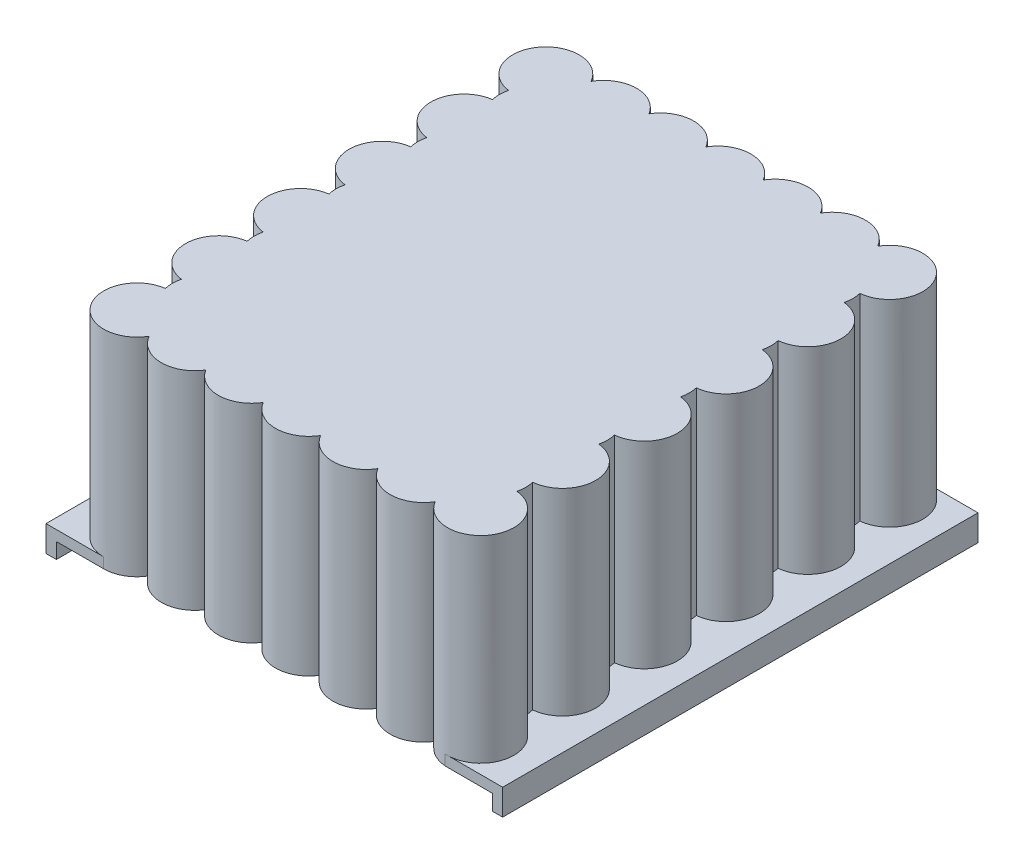
SolidWorks part; units mm, degrees
material "Titanium Ti-5Al-2.5Sn"
ref_plane "Front Plane" through (0, 0, 0) normal (0, 0, 1) x (1, 0, 0)
ref_plane "Top Plane" through (0, 0, 0) normal (0, 1, 0) x (1, 0, 0)
ref_plane "Right Plane" through (0, 0, 0) normal (1, 0, 0) x (0, 0, -1)
sketch "Sketch2" plane through (0, 0, 0) normal (0, 1, 0) x (1, 0, 0)
  circle A0 centre (-104.3845, 125.3413) radius 14
  circle A1 centre (-69.3845, 125.3413) radius 14
  circle A2 centre (-34.3845, 125.3413) radius 14
  circle A3 centre (0.6155, 125.3413) radius 14
  circle A4 centre (35.6155, 125.3413) radius 14
  circle A5 centre (70.6155, 125.3413) radius 14
  circle A6 centre (105.6155, 125.3413) radius 14
  circle A7 centre (-69.3845, 75.3413) radius 14
  circle A8 centre (-34.3845, 75.3413) radius 14
  circle A9 centre (0.6155, 75.3413) radius 14
  circle A10 centre (35.6155, 75.3413) radius 14
  circle A11 centre (70.6155, 75.3413) radius 14
  circle A12 centre (105.6155, 75.3413) radius 14
  circle A13 centre (-69.3845, 25.3413) radius 14
  circle A14 centre (-34.3845, 25.3413) radius 14
  circle A15 centre (0.6155, 25.3413) radius 14
  circle A16 centre (35.6155, 25.3413) radius 14
  circle A17 centre (70.6155, 25.3413) radius 14
  circle A18 centre (105.6155, 25.3413) radius 14
  circle A19 centre (-69.3845, -24.6587) radius 14
  circle A20 centre (-34.3845, -24.6587) radius 14
  circle A21 centre (0.6155, -24.6587) radius 14
  circle A22 centre (35.6155, -24.6587) radius 14
  circle A23 centre (70.6155, -24.6587) radius 14
  circle A24 centre (105.6155, -24.6587) radius 14
  circle A25 centre (-69.3845, -74.6587) radius 14
  circle A26 centre (-34.3845, -74.6587) radius 14
  circle A27 centre (0.6155, -74.6587) radius 14
  circle A28 centre (35.6155, -74.6587) radius 14
  circle A29 centre (70.6155, -74.6587) radius 14
  circle A30 centre (105.6155, -74.6587) radius 14
  circle A31 centre (-69.3845, -124.6587) radius 14
  circle A32 centre (-34.3845, -124.6587) radius 14
  circle A33 centre (0.6155, -124.6587) radius 14
  circle A34 centre (35.6155, -124.6587) radius 14
  circle A35 centre (70.6155, -124.6587) radius 14
  circle A36 centre (105.6155, -124.6587) radius 14
  circle A37 centre (-104.3845, 75.3413) radius 14
  circle A38 centre (-104.3845, 25.3413) radius 14
  circle A39 centre (-104.3845, -24.6587) radius 14
  circle A40 centre (-104.3845, -74.6587) radius 14
  circle A41 centre (-104.3845, -124.6587) radius 14
  circle A42 centre (-87.3845, 100.3413) radius 14
  circle A43 centre (-52.3845, 100.3413) radius 14
  circle A44 centre (-17.3845, 100.3413) radius 14
  circle A45 centre (17.6155, 100.3413) radius 14
  circle A46 centre (52.6155, 100.3413) radius 14
  circle A47 centre (87.6155, 100.3413) radius 14
  circle A48 centre (-52.3845, 50.3413) radius 14
  circle A49 centre (-17.3845, 50.3413) radius 14
  circle A50 centre (17.6155, 50.3413) radius 14
  circle A51 centre (52.6155, 50.3413) radius 14
  circle A52 centre (87.6155, 50.3413) radius 14
  circle A53 centre (-52.3845, 0.3413) radius 14
  circle A54 centre (-17.3845, 0.3413) radius 14
  circle A55 centre (17.6155, 0.3413) radius 14
  circle A56 centre (52.6155, 0.3413) radius 14
  circle A57 centre (87.6155, 0.3413) radius 14
  circle A58 centre (-52.3845, -49.6587) radius 14
  circle A59 centre (-17.3845, -49.6587) radius 14
  circle A60 centre (17.6155, -49.6587) radius 14
  circle A61 centre (52.6155, -49.6587) radius 14
  circle A62 centre (87.6155, -49.6587) radius 14
  circle A63 centre (-52.3845, -99.6587) radius 14
  circle A64 centre (-17.3845, -99.6587) radius 14
  circle A65 centre (17.6155, -99.6587) radius 14
  circle A66 centre (52.6155, -99.6587) radius 14
  circle A67 centre (87.6155, -99.6587) radius 14
  circle A68 centre (-87.3845, 50.3413) radius 14
  circle A69 centre (-87.3845, 0.3413) radius 14
  circle A70 centre (-87.3845, -49.6587) radius 14
  circle A71 centre (-87.3845, -99.6587) radius 14
sketch "Sketch3" plane through (0, 0, 0) normal (0, 1, 0) x (1, 0, 0)
  line L1 (-132.3198, 152.7914) -> (134.3802, 152.7914)
  line L2 (-132.3198, 152.7914) -> (-132.3198, -152.0086)
  line L3 (-132.3198, -152.0086) -> (134.3802, -152.0086)
  line L4 (134.3802, 152.7914) -> (134.3802, -152.0086)
  dimension "D1" = 304.8
  dimension "D2" = 266.7
extrude "Boss-Extrude1" add sketch "Sketch3" along normal blind 127
extrude "Cut-Extrude1" cut sketch "Sketch2" along normal blind 101.6
sketch "Sketch4" plane through (0, 0, 0) normal (0, -1, 0) x (1, 0, 0)
  line L1 (-132.3198, 152.0086) -> (134.3802, 152.0086)
  line L2 (-132.3198, 152.0086) -> (-132.3198, -152.7914)
  line L3 (-132.3198, -152.7914) -> (134.3802, -152.7914)
  line L4 (134.3802, 152.0086) -> (134.3802, -152.7914)
  arc A0 (-86.7752, 134.7985) -> (-107.1138, 104.5229) centre (-104.3845, 124.6587) ccw
  arc A5 (-16.7545, 114.3757) -> (-1.7647, 104.4976) centre (0.7715, 124.6587) ccw
  arc A7 (51.1245, 119.8835) -> (90.6148, 119.8357) centre (70.8755, 124.6587) ccw
  arc A8 (86.1781, 119.8771) -> (88.4015, 114.3757) centre (105.9275, 124.6587) ccw
  arc A9 (-49.6103, 79.513) -> (-51.8065, 84.9038) centre (-69.3325, 74.6207) ccw
  arc A10 (-51.8065, 84.9038) -> (-54.0268, 79.4152) centre (-34.2805, 74.6207) ccw
  arc A12 (33.3518, 54.4516) -> (33.3609, 94.791) centre (35.8235, 74.6207) ccw
  circle A13 centre (70.8755, 74.6207) radius 20.32
  arc A14 (88.4015, 84.9038) -> (88.4015, 64.3377) centre (105.9275, 74.6207) ccw
  arc A15 (-86.8585, 14.2997) -> (-84.6553, 19.7186) centre (-104.3845, 24.5827) ccw
  arc A16 (-89.0802, 29.3716) -> (-49.6012, 19.7272) centre (-69.3325, 24.5827) ccw
  arc A19 (16.071, 19.8137) -> (37.7142, 44.8146) centre (35.8235, 24.5827) ccw
  circle A20 centre (70.8755, 24.5827) radius 20.32
  arc A21 (88.4015, 34.8658) -> (88.4015, 14.2997) centre (105.9275, 24.5827) ccw
  arc A22 (-86.8585, -35.7383) -> (-86.8585, -15.1722) centre (-104.3845, -25.4553) ccw
  circle A23 centre (-69.3325, -25.4553) radius 20.32
  circle A24 centre (-34.2805, -25.4553) radius 20.32
  circle A25 centre (0.7715, -25.4553) radius 20.32
  circle A26 centre (35.8235, -25.4553) radius 20.32
  arc A27 (90.6057, -20.5953) -> (88.4015, -35.7383) centre (70.8755, -25.4553) ccw
  arc A28 (88.4015, -15.1722) -> (88.4015, -35.7383) centre (105.9275, -25.4553) ccw
  arc A29 (-86.8585, -85.7763) -> (-86.8585, -65.2102) centre (-104.3845, -75.4933) ccw
  circle A30 centre (-69.3325, -75.4933) radius 20.32
  circle A31 centre (-34.2805, -75.4933) radius 20.32
  circle A32 centre (0.7715, -75.4933) radius 20.32
  circle A33 centre (35.8235, -75.4933) radius 20.32
  circle A34 centre (70.8755, -75.4933) radius 20.32
  arc A35 (88.4015, -65.2102) -> (88.4015, -85.7763) centre (105.9275, -75.4933) ccw
  arc A36 (-84.6644, -120.6304) -> (-86.6147, -115.6754) centre (-104.3845, -125.5313) ccw
  arc A37 (-49.4244, -120.6136) -> (-88.6164, -120.7759) centre (-69.0004, -125.5313) ccw
  arc A38 (-14.5562, -120.6473) -> (-54.0268, -120.7368) centre (-34.2805, -125.5313) ccw
  arc A39 (20.4978, -120.6555) -> (-18.9734, -120.7311) centre (0.7715, -125.5313) ccw
  arc A40 (55.5518, -120.6635) -> (16.08, -120.7251) centre (35.8235, -125.5313) ccw
  arc A41 (90.6057, -120.6713) -> (51.1336, -120.7189) centre (70.8755, -125.5313) ccw
  arc A42 (88.4015, -115.2482) -> (86.1871, -120.7126) centre (105.9275, -125.5313) ccw
  arc A43 (-107.1138, 104.5229) -> (-107.1047, 94.7578) centre (-87.3845, 99.6587) ccw
  arc A44 (-54.0268, 79.4152) -> (-34.7069, 89.4325) centre (-52.2661, 99.6587) ccw
  arc A47 (33.3609, 94.791) -> (35.53, 109.885) centre (53.0892, 99.6587) ccw
  arc A48 (90.6148, 119.8357) -> (90.6057, 79.4807) centre (88.2076, 99.6587) ccw
  arc A49 (-89.0802, 29.3716) -> (-84.6644, 29.4836) centre (-87.3845, 49.6207) ccw
  arc A50 (-69.8253, 59.847) -> (-71.9974, 54.4762) centre (-52.2661, 49.6207) ccw
  arc A51 (-34.7069, 59.847) -> (-36.8811, 54.4678) centre (-17.1477, 49.6207) ccw
  arc A52 (35.53, 39.3945) -> (33.3518, 54.4516) centre (53.0892, 49.6207) ccw
  arc A53 (90.6148, 69.7977) -> (90.6057, 29.4427) centre (88.2076, 49.6207) ccw
  arc A54 (20.4978, 29.4585) -> (35.53, 39.3945) centre (17.9708, 49.6207) ccw
  arc A55 (-89.0802, -20.6664) -> (-89.0891, 19.8311) centre (-87.3845, -0.4173) ccw
  circle A56 centre (-52.2661, -0.4173) radius 20.32
  arc A57 (-14.5471, 19.7356) -> (-18.9824, 19.8197) centre (-17.1477, -0.4173) ccw
  circle A58 centre (53.0892, -0.4173) radius 20.32
  arc A59 (90.6148, 19.7597) -> (90.6057, -20.5953) centre (88.2076, -0.4173) ccw
  circle A60 centre (17.9708, -0.4173) radius 20.32
  arc A61 (-89.0802, -70.7044) -> (-89.0891, -30.2069) centre (-87.3845, -50.4553) ccw
  circle A62 centre (-52.2661, -50.4553) radius 20.32
  circle A63 centre (-17.1477, -50.4553) radius 20.32
  circle A64 centre (53.0892, -50.4553) radius 20.32
  arc A65 (86.1781, -30.2369) -> (90.6057, -70.6333) centre (88.2076, -50.4553) ccw
  circle A66 centre (17.9708, -50.4553) radius 20.32
  arc A67 (-88.6164, -120.7759) -> (-89.0891, -80.2449) centre (-87.3845, -100.4933) ccw
  circle A68 centre (-52.2661, -100.4933) radius 20.32
  circle A69 centre (-17.1477, -100.4933) radius 20.32
  circle A70 centre (53.0892, -100.4933) radius 20.32
  arc A71 (90.6148, -80.3163) -> (90.6057, -120.6713) centre (88.2076, -100.4933) ccw
  circle A72 centre (17.9708, -100.4933) radius 20.32
  arc A74 (-89.0891, 119.9071) -> (-86.8585, 114.3757) centre (-69.3325, 124.6587) ccw
  arc A76 (-32.5108, 104.4159) -> (-34.7069, 109.885) centre (-52.2661, 99.6587) ccw
  arc A78 (-67.6279, 54.3724) -> (-69.8253, 59.847) centre (-87.3845, 49.6207) ccw
  arc A79 (-67.6369, 44.8319) -> (-71.9884, 44.7284) centre (-69.3325, 24.5827) ccw
  arc A80 (-49.6103, 29.475) -> (-51.8065, 34.8658) centre (-69.3325, 24.5827) ccw
  arc A81 (-1.7556, 94.783) -> (0.4116, 89.4325) centre (17.9708, 99.6587) ccw
  arc A82 (-34.7069, 109.885) -> (-36.8811, 104.5058) centre (-17.1477, 99.6587) ccw
  arc A83 (-54.0358, 19.8255) -> (-16.7545, 14.2997) centre (-34.2805, 24.5827) ccw
  arc A84 (-36.8811, 104.5058) -> (-32.5108, 104.4159) centre (-34.2805, 124.6587) ccw
  arc A85 (-51.5561, 135.3572) -> (-86.7752, 134.7985) centre (-69.0004, 124.6587) ccw
  arc A86 (-16.7545, 134.9418) -> (-51.5561, 135.3572) centre (-34.2805, 124.6587) ccw
  arc A87 (18.2975, 134.9418) -> (-16.7545, 134.9418) centre (0.7715, 124.6587) ccw
  arc A88 (53.3495, 134.9418) -> (18.2975, 134.9418) centre (35.8235, 124.6587) ccw
  arc A89 (88.4015, 134.9418) -> (53.3495, 134.9418) centre (70.8755, 124.6587) ccw
  arc A90 (107.957, 104.4403) -> (88.4015, 134.9418) centre (105.9275, 124.6587) ccw
  arc A91 (107.948, 94.84) -> (107.957, 104.4403) centre (88.2076, 99.6587) ccw
  arc A92 (107.957, 54.4023) -> (107.948, 94.84) centre (105.9275, 74.6207) ccw
  arc A93 (107.948, 44.802) -> (107.957, 54.4023) centre (88.2076, 49.6207) ccw
  arc A94 (107.957, 4.3643) -> (107.948, 44.802) centre (105.9275, 24.5827) ccw
  arc A95 (107.948, -5.236) -> (107.957, 4.3643) centre (88.2076, -0.4173) ccw
  arc A96 (107.957, -45.6737) -> (107.948, -5.236) centre (105.9275, -25.4553) ccw
  arc A97 (107.948, -55.274) -> (107.957, -45.6737) centre (88.2076, -50.4553) ccw
  arc A98 (107.957, -95.7117) -> (107.948, -55.274) centre (105.9275, -75.4933) ccw
  arc A99 (107.948, -105.312) -> (107.957, -95.7117) centre (88.2076, -100.4933) ccw
  arc A100 (88.4015, -135.8143) -> (107.948, -105.312) centre (105.9275, -125.5313) ccw
  arc A101 (53.3495, -135.8143) -> (88.4015, -135.8143) centre (70.8755, -125.5313) ccw
  arc A102 (18.2975, -135.8143) -> (53.3495, -135.8143) centre (35.8235, -125.5313) ccw
  arc A103 (-16.7545, -135.8143) -> (18.2975, -135.8143) centre (0.7715, -125.5313) ccw
  arc A104 (-51.7196, -135.961) -> (-16.7545, -135.8143) centre (-34.2805, -125.5313) ccw
  arc A105 (-86.6147, -135.3871) -> (-51.7196, -135.961) centre (-69.0004, -125.5313) ccw
  arc A106 (-107.1047, -105.3942) -> (-86.6147, -135.3871) centre (-104.3845, -125.5313) ccw
  arc A107 (-107.1138, -95.6291) -> (-107.1047, -105.3942) centre (-87.3845, -100.4933) ccw
  arc A108 (-107.1047, -55.3562) -> (-107.1138, -95.6291) centre (-104.3845, -75.4933) ccw
  arc A109 (-107.1138, -45.5911) -> (-107.1047, -55.3562) centre (-87.3845, -50.4553) ccw
  arc A110 (-107.1047, -5.3182) -> (-107.1138, -45.5911) centre (-104.3845, -25.4553) ccw
  arc A111 (-107.1138, 4.4469) -> (-107.1047, -5.3182) centre (-87.3845, -0.4173) ccw
  arc A112 (-107.1047, 44.7198) -> (-107.1138, 4.4469) centre (-104.3845, 24.5827) ccw
  arc A113 (-107.1138, 54.4849) -> (-107.1047, 44.7198) centre (-87.3845, 49.6207) ccw
  arc A114 (-34.7069, 9.809) -> (0.4116, 9.809) centre (-17.1477, -0.4173) ccw
  arc A115 (-107.1047, 94.7578) -> (-107.1138, 54.4849) centre (-104.3845, 74.6207) ccw
  arc A116 (-16.7545, 114.3757) -> (-14.5471, 119.8116) centre (-34.2805, 124.6587) ccw
  arc A117 (0.4116, 109.885) -> (-1.7647, 104.4976) centre (17.9708, 99.6587) ccw
  arc A119 (37.7232, 104.4277) -> (55.5609, 119.8278) centre (35.8235, 124.6587) ccw
  arc A120 (-34.7069, 89.4325) -> (-18.9734, 79.4209) centre (-17.1477, 99.6587) ccw
  arc A122 (20.5069, 69.7818) -> (20.4978, 79.4965) centre (0.7715, 74.6207) ccw
  arc A124 (-14.5471, 69.7736) -> (-18.9824, 69.8577) centre (-17.1477, 49.6207) ccw
  arc A125 (-54.0358, 69.8635) -> (-32.5108, 54.3779) centre (-34.2805, 74.6207) ccw
  arc A127 (-71.9974, 54.4762) -> (-67.6279, 54.3724) centre (-69.3325, 74.6207) ccw
  arc A132 (-86.8585, 64.3377) -> (-84.6553, 69.7566) centre (-104.3845, 74.6207) ccw
  arc A133 (-51.8065, 64.3377) -> (-49.6012, 69.7652) centre (-69.3325, 74.6207) ccw
  arc A134 (-18.9734, 29.3829) -> (-14.5562, 29.4667) centre (-17.1477, 49.6207) ccw
  arc A135 (-32.5108, 54.3779) -> (-54.0358, 69.8635) centre (-52.2661, 49.6207) ccw
  arc A137 (37.7142, 44.8146) -> (35.53, 59.847) centre (17.9708, 49.6207) ccw
  arc A139 (33.3609, 44.753) -> (18.2975, 34.8658) centre (35.8235, 24.5827) ccw
  arc A140 (-16.7545, 14.2997) -> (20.4978, 29.4585) centre (0.7715, 24.5827) ccw
  arc A141 (20.5069, 69.7818) -> (-1.7647, 54.4596) centre (17.9708, 49.6207) ccw
  arc A142 (35.53, 89.4325) -> (37.7232, 104.4277) centre (17.9708, 99.6587) ccw
  arc A145 (-18.9824, 69.8577) -> (-16.7545, 64.3377) centre (0.7715, 74.6207) ccw
  arc A146 (16.08, 79.4269) -> (20.4978, 79.4965) centre (17.9708, 99.6587) ccw
  arc A148 (16.071, 119.8897) -> (18.2975, 114.3757) centre (35.8235, 124.6587) ccw
  arc A149 (-16.7545, 34.8658) -> (-18.9734, 29.3829) centre (0.7715, 24.5827) ccw
  point P8 (0, 0)
  dimension "D1" = 40.64
  dimension "D2" = 7
  dimension "D4" = 40.64
  dimension "D3" = 6
  dimension "D5" = 6
  dimension "D6" = 5
sketch "Sketch5" plane through (0, 0, 0) normal (0, -1, 0) x (1, 0, 0)
  line L0 (-132.3198, 152.0086) -> (-132.3198, -152.7914) construction
  line L1 (-132.3198, -152.7914) -> (134.3802, -152.7914) construction
  line L2 (134.3802, 152.0086) -> (134.3802, -152.7914) construction
  line L3 (-132.3198, 152.0086) -> (134.3802, 152.0086) construction
  line L4 (-132.3198, 152.0086) -> (-132.3198, -152.7914)
  line L5 (-132.3198, -152.7914) -> (134.3802, -152.7914)
  line L6 (134.3802, 152.0086) -> (134.3802, -152.7914)
  line L7 (-132.3198, 152.0086) -> (134.3802, 152.0086)
  arc A0 (-86.7752, 134.7985) -> (-107.1138, 104.5229) centre (-104.3845, 124.6587) ccw construction
  arc A1 (-107.1138, 104.5229) -> (-107.1047, 94.7578) centre (-87.3845, 99.6587) ccw construction
  arc A2 (-107.1047, 94.7578) -> (-107.1138, 54.4849) centre (-104.3845, 74.6207) ccw construction
  arc A3 (-107.1138, 54.4849) -> (-107.1047, 44.7198) centre (-87.3845, 49.6207) ccw construction
  arc A4 (-107.1047, 44.7198) -> (-107.1138, 4.4469) centre (-104.3845, 24.5827) ccw construction
  arc A5 (-107.1138, 4.4469) -> (-107.1047, -5.3182) centre (-87.3845, -0.4173) ccw construction
  arc A6 (-107.1047, -5.3182) -> (-107.1138, -45.5911) centre (-104.3845, -25.4553) ccw construction
  arc A7 (-107.1138, -45.5911) -> (-107.1047, -55.3562) centre (-87.3845, -50.4553) ccw construction
  arc A8 (-107.1047, -55.3562) -> (-107.1138, -95.6291) centre (-104.3845, -75.4933) ccw construction
  arc A9 (-107.1138, -95.6291) -> (-107.1047, -105.3942) centre (-87.3845, -100.4933) ccw construction
  arc A10 (-107.1047, -105.3942) -> (-86.6147, -135.3871) centre (-104.3845, -125.5313) ccw construction
  arc A11 (-86.6147, -135.3871) -> (-51.7196, -135.961) centre (-69.0004, -125.5313) ccw construction
  arc A12 (-51.7196, -135.961) -> (-16.7545, -135.8143) centre (-34.2805, -125.5313) ccw construction
  arc A13 (-16.7545, -135.8143) -> (18.2975, -135.8143) centre (0.7715, -125.5313) ccw construction
  arc A14 (18.2975, -135.8143) -> (53.3495, -135.8143) centre (35.8235, -125.5313) ccw construction
  arc A15 (53.3495, -135.8143) -> (88.4015, -135.8143) centre (70.8755, -125.5313) ccw construction
  arc A16 (88.4015, -135.8143) -> (107.948, -105.312) centre (105.9275, -125.5313) ccw construction
  arc A17 (107.948, -105.312) -> (107.957, -95.7117) centre (88.2076, -100.4933) ccw construction
  arc A18 (107.957, -95.7117) -> (107.948, -55.274) centre (105.9275, -75.4933) ccw construction
  arc A19 (107.948, -55.274) -> (107.957, -45.6737) centre (88.2076, -50.4553) ccw construction
  arc A20 (107.957, -45.6737) -> (107.948, -5.236) centre (105.9275, -25.4553) ccw construction
  arc A21 (107.948, -5.236) -> (107.957, 4.3643) centre (88.2076, -0.4173) ccw construction
  arc A22 (107.957, 4.3643) -> (107.948, 44.802) centre (105.9275, 24.5827) ccw construction
  arc A23 (107.948, 44.802) -> (107.957, 54.4023) centre (88.2076, 49.6207) ccw construction
  arc A24 (107.957, 54.4023) -> (107.948, 94.84) centre (105.9275, 74.6207) ccw construction
  arc A25 (107.948, 94.84) -> (107.957, 104.4403) centre (88.2076, 99.6587) ccw construction
  arc A26 (107.957, 104.4403) -> (88.4015, 134.9418) centre (105.9275, 124.6587) ccw construction
  arc A27 (88.4015, 134.9418) -> (53.3495, 134.9418) centre (70.8755, 124.6587) ccw construction
  arc A28 (53.3495, 134.9418) -> (18.2975, 134.9418) centre (35.8235, 124.6587) ccw construction
  arc A29 (18.2975, 134.9418) -> (-16.7545, 134.9418) centre (0.7715, 124.6587) ccw construction
  arc A30 (-16.7545, 134.9418) -> (-51.5561, 135.3572) centre (-34.2805, 124.6587) ccw construction
  arc A31 (-51.5561, 135.3572) -> (-86.7752, 134.7985) centre (-69.0004, 124.6587) ccw construction
  arc A32 (-86.7752, 134.7985) -> (-107.1138, 104.5229) centre (-104.3845, 124.6587) ccw
  arc A33 (-107.1138, 104.5229) -> (-107.1047, 94.7578) centre (-87.3845, 99.6587) ccw
  arc A34 (-107.1047, 94.7578) -> (-107.1138, 54.4849) centre (-104.3845, 74.6207) ccw
  arc A35 (-107.1138, 54.4849) -> (-107.1047, 44.7198) centre (-87.3845, 49.6207) ccw
  arc A36 (-107.1047, 44.7198) -> (-107.1138, 4.4469) centre (-104.3845, 24.5827) ccw
  arc A37 (-107.1138, 4.4469) -> (-107.1047, -5.3182) centre (-87.3845, -0.4173) ccw
  arc A38 (-107.1047, -5.3182) -> (-107.1138, -45.5911) centre (-104.3845, -25.4553) ccw
  arc A39 (-107.1138, -45.5911) -> (-107.1047, -55.3562) centre (-87.3845, -50.4553) ccw
  arc A40 (-107.1047, -55.3562) -> (-107.1138, -95.6291) centre (-104.3845, -75.4933) ccw
  arc A41 (-107.1138, -95.6291) -> (-107.1047, -105.3942) centre (-87.3845, -100.4933) ccw
  arc A42 (-107.1047, -105.3942) -> (-86.6147, -135.3871) centre (-104.3845, -125.5313) ccw
  arc A43 (-86.6147, -135.3871) -> (-51.7196, -135.961) centre (-69.0004, -125.5313) ccw
  arc A44 (-51.7196, -135.961) -> (-16.7545, -135.8143) centre (-34.2805, -125.5313) ccw
  arc A45 (-16.7545, -135.8143) -> (18.2975, -135.8143) centre (0.7715, -125.5313) ccw
  arc A46 (18.2975, -135.8143) -> (53.3495, -135.8143) centre (35.8235, -125.5313) ccw
  arc A47 (53.3495, -135.8143) -> (88.4015, -135.8143) centre (70.8755, -125.5313) ccw
  arc A48 (88.4015, -135.8143) -> (107.948, -105.312) centre (105.9275, -125.5313) ccw
  arc A49 (107.948, -105.312) -> (107.957, -95.7117) centre (88.2076, -100.4933) ccw
  arc A50 (107.957, -95.7117) -> (107.948, -55.274) centre (105.9275, -75.4933) ccw
  arc A51 (107.948, -55.274) -> (107.957, -45.6737) centre (88.2076, -50.4553) ccw
  arc A52 (107.957, -45.6737) -> (107.948, -5.236) centre (105.9275, -25.4553) ccw
  arc A53 (107.948, -5.236) -> (107.957, 4.3643) centre (88.2076, -0.4173) ccw
  arc A54 (107.957, 4.3643) -> (107.948, 44.802) centre (105.9275, 24.5827) ccw
  arc A55 (107.948, 44.802) -> (107.957, 54.4023) centre (88.2076, 49.6207) ccw
  arc A56 (107.957, 54.4023) -> (107.948, 94.84) centre (105.9275, 74.6207) ccw
  arc A57 (107.948, 94.84) -> (107.957, 104.4403) centre (88.2076, 99.6587) ccw
  arc A58 (107.957, 104.4403) -> (88.4015, 134.9418) centre (105.9275, 124.6587) ccw
  arc A59 (88.4015, 134.9418) -> (53.3495, 134.9418) centre (70.8755, 124.6587) ccw
  arc A60 (53.3495, 134.9418) -> (18.2975, 134.9418) centre (35.8235, 124.6587) ccw
  arc A61 (18.2975, 134.9418) -> (-16.7545, 134.9418) centre (0.7715, 124.6587) ccw
  arc A62 (-16.7545, 134.9418) -> (-51.5561, 135.3572) centre (-34.2805, 124.6587) ccw
  arc A63 (-51.5561, 135.3572) -> (-86.7752, 134.7985) centre (-69.0004, 124.6587) ccw
extrude "Cut-Extrude2" cut sketch "Sketch5" against normal through all
sketch "Sketch6" plane through (0, 0, 0) normal (0, -1, 0) x (1, 0, 0)
  line L0 (-104.3845, 144.9787) -> (-139.7, 144.9787)
  line L1 (-139.7, 144.9787) -> (-139.7, -145.8513)
  line L2 (-104.3845, -145.8513) -> (-139.7, -145.8513)
  line L3 (0, -69.85) -> (0, 69.85) construction
  arc A0 (-107.1047, -105.3942) -> (-86.6147, -135.3871) centre (-104.3845, -125.5313) ccw construction
  arc A1 (-107.1138, -95.6291) -> (-107.1047, -105.3942) centre (-87.3845, -100.4933) ccw construction
  arc A2 (-107.1047, -55.3562) -> (-107.1138, -95.6291) centre (-104.3845, -75.4933) ccw construction
  arc A3 (-107.1138, -45.5911) -> (-107.1047, -55.3562) centre (-87.3845, -50.4553) ccw construction
  arc A4 (-107.1047, -5.3182) -> (-107.1138, -45.5911) centre (-104.3845, -25.4553) ccw construction
  arc A5 (-107.1138, 4.4469) -> (-107.1047, -5.3182) centre (-87.3845, -0.4173) ccw construction
  arc A6 (-107.1047, 44.7198) -> (-107.1138, 4.4469) centre (-104.3845, 24.5827) ccw construction
  arc A7 (-107.1138, 54.4849) -> (-107.1047, 44.7198) centre (-87.3845, 49.6207) ccw construction
  arc A8 (-107.1047, 94.7578) -> (-107.1138, 54.4849) centre (-104.3845, 74.6207) ccw construction
  arc A9 (-107.1138, 104.5229) -> (-107.1047, 94.7578) centre (-87.3845, 99.6587) ccw construction
  arc A10 (-86.7752, 134.7985) -> (-107.1138, 104.5229) centre (-104.3845, 124.6587) ccw construction
  arc A11 (-107.1047, -105.3942) -> (-104.3845, -145.8513) centre (-104.3845, -125.5313) ccw
  arc A12 (-107.1138, -95.6291) -> (-107.1047, -105.3942) centre (-87.3845, -100.4933) ccw
  arc A13 (-107.1047, -55.3562) -> (-107.1138, -95.6291) centre (-104.3845, -75.4933) ccw
  arc A14 (-107.1138, -45.5911) -> (-107.1047, -55.3562) centre (-87.3845, -50.4553) ccw
  arc A15 (-107.1047, -5.3182) -> (-107.1138, -45.5911) centre (-104.3845, -25.4553) ccw
  arc A16 (-107.1138, 4.4469) -> (-107.1047, -5.3182) centre (-87.3845, -0.4173) ccw
  arc A17 (-107.1047, 44.7198) -> (-107.1138, 4.4469) centre (-104.3845, 24.5827) ccw
  arc A18 (-107.1138, 54.4849) -> (-107.1047, 44.7198) centre (-87.3845, 49.6207) ccw
  arc A19 (-107.1047, 94.7578) -> (-107.1138, 54.4849) centre (-104.3845, 74.6207) ccw
  arc A20 (-107.1138, 104.5229) -> (-107.1047, 94.7578) centre (-87.3845, 99.6587) ccw
  arc A21 (-104.3845, 144.9787) -> (-107.1138, 104.5229) centre (-104.3845, 124.6587) ccw
  point P28 (-141.2215, -143.3546)
  dimension "D1" = 139.7
extrude "Boss-Extrude2" add sketch "Sketch6" against normal blind 6.35
mirror "Mirror2" about plane through (0, 0, 0) normal (1, 0, 0) of "Boss-Extrude2"
ref_plane "Plane1" through (0, 0, -145.8513) normal (0, 0, -1) x (-1, 0, 0)
sketch "Sketch7" plane through (0, 0, -145.8513) normal (0, 0, -1) x (-1, 0, 0)
  line L1 (-44.45, 88.9) -> (44.45, 88.9)
  line L2 (-44.45, 88.9) -> (-44.45, 25.4)
  line L3 (-44.45, 25.4) -> (44.45, 25.4)
  line L4 (44.45, 88.9) -> (44.45, 25.4)
  dimension "D1" = 44.45
  dimension "D2" = 88.9
  dimension "D3" = 25.4
  dimension "D4" = 63.5
extrude "Boss-Extrude4" [suppressed] add sketch "Sketch7" along normal blind 6.35 separate body
fillet "Fillet1" [suppressed] radius 2.54
fillet "Fillet2" [suppressed] radius 2.54
sketch "Sketch10" plane through (0, 0, 0) normal (0, -1, 0) x (1, 0, 0)
  line L0 (-104.3845, 144.9787) -> (-139.7, 144.9787) construction
  line L1 (-139.7, -145.8513) -> (-133.35, -145.8513)
  line L2 (-139.7, -145.8513) -> (-139.7, 144.9787)
  line L3 (-139.7, 144.9787) -> (-133.35, 144.9787)
  line L4 (-133.35, -145.8513) -> (-133.35, 144.9787)
  dimension "D1" = 6.35
extrude "Boss-Extrude5" add sketch "Sketch10" along normal blind 9.525
mirror "Mirror3" about plane through (0, 0, 0) normal (1, 0, 0) of "Boss-Extrude5"
